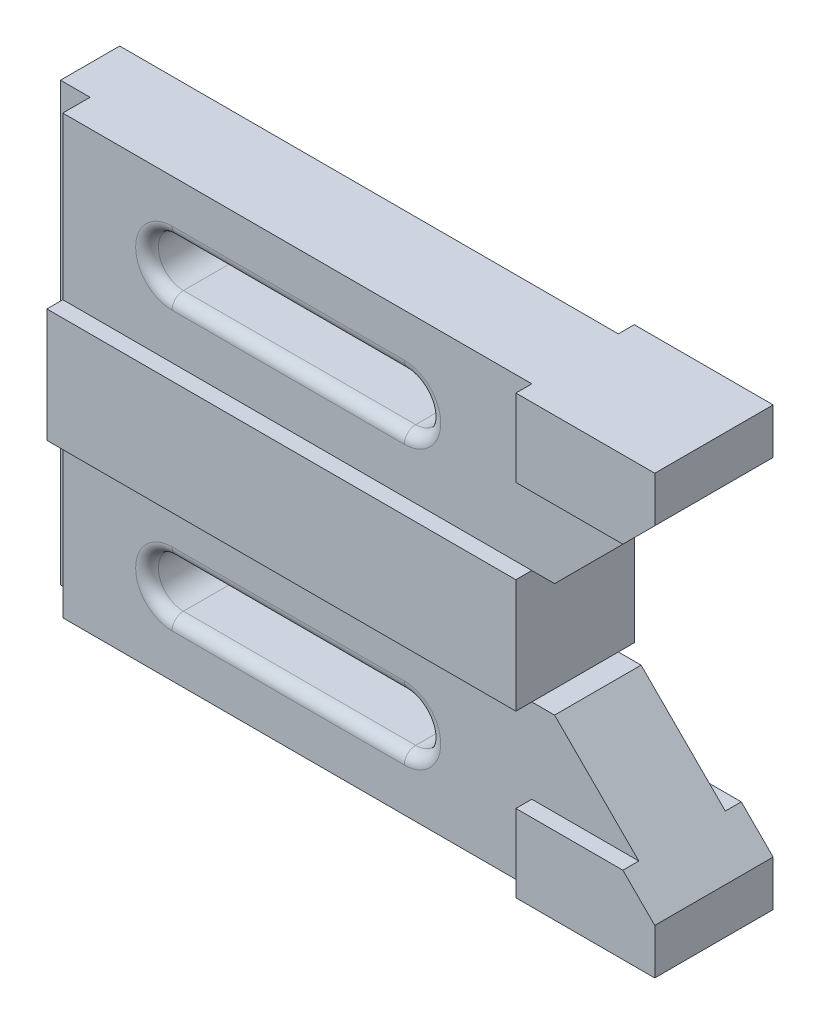
SolidWorks part; units mm, degrees
material "1060 Alloy"
ref_plane "Front Plane" through (0, 0, 0) normal (0, 0, 1) x (1, 0, 0)
ref_plane "Top Plane" through (0, 0, 0) normal (0, 1, 0) x (1, 0, 0)
ref_plane "Right Plane" through (0, 0, 0) normal (1, 0, 0) x (0, 0, -1)
sketch "Sketch1" plane through (0, 0, 0) normal (0, 0, 1) x (1, 0, 0)
  line L0 (0, -138.741) -> (0, 138.741) construction
  line L1 (-180.2878, 0) -> (180.2878, 0) construction
  line L2 (140, 48) -> (140, 38)
  line L7 (0, 48) -> (140, 48)
  line L8 (0, 48) -> (0, -48)
  line L9 (0, -48) -> (140, -48)
  line L10 (140, 48) -> (140, 38)
  line L11 (114.5, 12.5) -> (109.5, 12.5)
  line L12 (140, 38) -> (114.5, 12.5)
  line L13 (140, 48) -> (104.5, 48)
  line L14 (104.5, 48) -> (104.5, 31)
  line L15 (104.5, 31) -> (133, 31)
  line L16 (109.5, 12.5) -> (0, 12.5)
  line L17 (30.5, 30.5) -> (81.5, 30.5) construction
  line L18 (30.5, 36) -> (81.5, 36)
  line L19 (30.5, 25) -> (81.5, 25)
  line L20 (109.5, -12.5) -> (0, -12.5)
  line L21 (114.5, -12.5) -> (109.5, -12.5)
  line L22 (140, -38) -> (114.5, -12.5)
  line L23 (104.5, -48) -> (104.5, -31)
  line L24 (104.5, -31) -> (133, -31)
  line L25 (30.5, -30.5) -> (81.5, -30.5) construction
  line L26 (30.5, -36) -> (81.5, -36)
  line L27 (30.5, -25) -> (81.5, -25)
  line L28 (109.5, 12.5) -> (109.5, -12.5)
  line L29 (140, -38) -> (140, -48)
  arc A0 (30.5, 36) -> (30.5, 25) centre (30.5, 30.5) ccw
  arc A1 (81.5, 25) -> (81.5, 36) centre (81.5, 30.5) ccw
  arc A2 (30.5, -36) -> (30.5, -25) centre (30.5, -30.5) cw
  arc A3 (81.5, -25) -> (81.5, -36) centre (81.5, -30.5) cw
  point P4 (0, 0)
  point P8 (0, 0)
  point P11 (0, 0)
  point P22 (56, 30.5)
  point P37 (56, -30.5)
  dimension "D11" = 5.5
  dimension "D1" = 140
  dimension "D2" = 96
  dimension "D3" = 10
  dimension "D4" = 114.5
  dimension "D5" = 5
  dimension "D6" = 45
  dimension "D7" = 35.5
  dimension "D8" = 17
  dimension "D9" = 30.5
  dimension "D10" = 17.5
  dimension "D12" = 51
extrude "Boss-Extrude3" add sketch "Sketch1" along normal mid plane 19 contours L16 L11 L12 L15 L14 L7 L8 A1 L19 A0 L18 | L19 A1 L18 A0 | L14 L15 L12 L2 L7 | L28 L16 L8 L20 | L29 L22 L24 L23 L9 | L23 L24 L22 L21 L20 L8 L9 L27 A3 L26 A2 | A3 L27 A2 L26
sketch "Sketch9" plane through (0, 0, 9.5) normal (0, 0, 1) x (1, 0, 0)
  line L0 (140, 48) -> (140, 38)
  line L1 (140, 38) -> (133, 31)
  line L4 (0, 48) -> (140, 48) construction
  line L5 (109.5, 48) -> (140, 48)
  line L6 (109.5, 48) -> (109.5, 31)
  line L7 (109.5, 31) -> (133, 31)
  dimension "D1" = 17
  dimension "D2" = 30.5
  dimension "D3" = 7
extrude "Boss-Extrude4" add sketch "Sketch9" along normal mid plane 7
sketch "Sketch10" plane through (0, 0, -9.5) normal (0, 0, -1) x (-1, 0, 0)
  line L0 (-140, 48) -> (-140, 38)
  line L2 (-114.5, 12.5) -> (-109.5, 12.5)
  line L4 (-109.5, 48) -> (-140, 48)
  line L5 (-109.5, 48) -> (-109.5, 31)
  line L6 (-109.5, 31) -> (-133, 31)
  line L7 (-133, 31) -> (-140, 38)
  line M4 (-140, 38) -> (-114.5, 12.5)
  line M12 (0, 48) -> (-140, 48)
  line M13 (-140, 48) -> (-140, 38)
  dimension "D1" = 17
  dimension "D2" = 23.5
  dimension "D3" = 9.8995
extrude "Boss-Extrude5" add sketch "Sketch10" along normal mid plane 7 contours L6 L5 M12 M13 M4
sketch "Sketch11" plane through (0, 0, 9.5) normal (0, 0, 1) x (1, 0, 0)
  line L0 (140, -38) -> (140, -48)
  line L1 (140, -48) -> (109.5, -48)
  line L2 (0, -48) -> (140, -48) construction
  line L3 (109.5, -48) -> (109.5, -31)
  line L4 (109.5, -31) -> (133, -31)
  line L5 (140, -38) -> (114.5, -12.5) construction
  line L6 (133, -31) -> (140, -38)
  dimension "D1" = 30.5
  dimension "D2" = 17
extrude "Boss-Extrude6" add sketch "Sketch11" along normal mid plane 7
sketch "Sketch12" plane through (0, 0, -9.5) normal (0, 0, -1) x (-1, 0, 0)
  line L0 (-140, -48) -> (-140, -38)
  line L1 (-140, -38) -> (-140, -48) construction
  line L2 (-140, -38) -> (-133, -31)
  line L3 (-140, -38) -> (-114.5, -12.5) construction
  line L4 (-133, -31) -> (-109.5, -31)
  line L5 (-109.5, -31) -> (-109.5, -48)
  line L6 (0, -48) -> (-140, -48) construction
  line L7 (-109.5, -48) -> (-140, -48)
  dimension "D1" = 30.5
  dimension "D2" = 17
extrude "Boss-Extrude7" add sketch "Sketch12" along normal mid plane 7
sketch "Sketch13" plane through (0, 0, 9.5) normal (0, 0, 1) x (1, 0, 0)
  line L0 (0, 48) -> (0, -48) construction
  line L1 (109.5, 12.5) -> (0, 12.5)
  line L2 (109.5, 12.5) -> (109.5, -12.5)
  line L3 (109.5, -12.5) -> (0, -12.5)
  line L4 (0, 12.5) -> (0, -12.5)
  dimension "D1" = 25
extrude "Boss-Extrude8" add sketch "Sketch13" along normal mid plane 7
sketch "Sketch14" plane through (0, 0, -9.5) normal (0, 0, -1) x (-1, 0, 0)
  line L1 (-109.5, 12.5) -> (0, 12.5)
  line L2 (-109.5, 12.5) -> (-109.5, -12.5)
  line L3 (-109.5, -12.5) -> (0, -12.5)
  line L4 (0, 12.5) -> (0, -12.5)
extrude "Boss-Extrude9" add sketch "Sketch14" along normal mid plane 7
sketch "Sketch15" plane through (0, 0, 9.5) normal (0, 0, 1) x (1, 0, 0)
  line L0 (30.5, 30.5) -> (81.5, 30.5) construction
  line L1 (30.5, 36) -> (81.5, 36)
  line L2 (30.5, 25) -> (81.5, 25)
  line L3 (0, 48) -> (0, 12.5) construction
  line L4 (0, 48) -> (109.5, 48) construction
  line L5 (30.5, -30.5) -> (81.5, -30.5) construction
  line L6 (30.5, -25) -> (81.5, -25)
  line L7 (30.5, -36) -> (81.5, -36)
  line L8 (0, -48) -> (109.5, -48) construction
  line L9 (0, -12.5) -> (0, -48) construction
  arc A0 (30.5, 36) -> (30.5, 25) centre (30.5, 30.5) ccw
  arc A1 (81.5, 25) -> (81.5, 36) centre (81.5, 30.5) ccw
  arc A2 (30.5, -25) -> (30.5, -36) centre (30.5, -30.5) ccw
  arc A3 (81.5, -36) -> (81.5, -25) centre (81.5, -30.5) ccw
  point P2 (56, 30.5)
  point P9 (56, -30.5)
  dimension "D1" = 5.5
  dimension "D7" = 5.5
  dimension "D2" = 30.5
  dimension "D3" = 17.5
  dimension "D4" = 51
  dimension "D5" = 51
  dimension "D6" = 17.5
  dimension "D8" = 30.5
extrude "Cut-Extrude1" cut sketch "Sketch15" against normal blind 44
fillet "Fillet1" radius 2.5 16 edges at (87, -30.5, 9.5) (25, -30.5, 9.5) (56, -36, 9.5) (56, -25, 9.5) (25, -30.5, -9.5) (56, -25, -9.5) (87, -30.5, -9.5) (56, -36, -9.5) (87, 30.5, 9.5) (87, 30.5, -9.5) (56, 36, 9.5) (56, 36, -9.5) (56, 25, 9.5) (25, 30.5, 9.5) (25, 30.5, -9.5) (56, 25, -9.5)
ref_plane "Plane1" through (0, 0, 15) normal (0, 0, 1) x (1, 0, 0)
sketch "Sketch16" plane through (0, 0, 15) normal (0, 0, 1) x (1, 0, 0)
  line L0 (0, -48) -> (109.5, -48) construction
  line L1 (0, 48) -> (6.5, 48)
  line L2 (0, 48) -> (0, -48)
  line L3 (0, -48) -> (6.5, -48)
  line L4 (6.5, 48) -> (6.5, -48)
  dimension "D1" = 6.5
extrude "Cut-Extrude2" cut sketch "Sketch16" against normal blind 11.5
